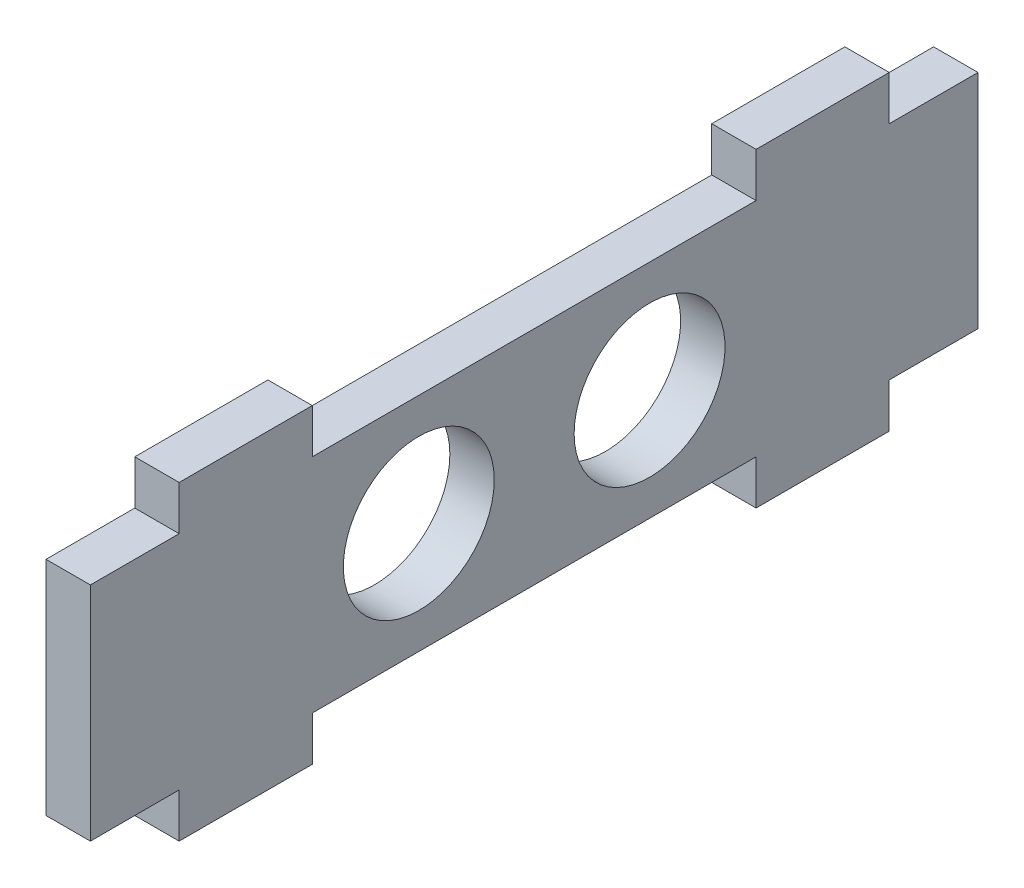
SolidWorks part; units mm, degrees
ref_plane "Front Plane" through (0, 0, 0) normal (0, 0, 1) x (1, 0, 0)
ref_plane "Top Plane" through (0, 0, 0) normal (0, 1, 0) x (1, 0, 0)
ref_plane "Right Plane" through (0, 0, 0) normal (1, 0, 0) x (0, 0, -1)
sketch "Sketch2" plane through (0, 0, 0) normal (1, 0, 0) x (0, 0, -1)
  line L0 (0, -4.3058) -> (0, 5.8448) construction
  line L1 (-50, -12.5) -> (-40, -12.5)
  line L2 (-50, -12.5) -> (-50, 12.5)
  line L3 (-50, 12.5) -> (-40, 12.5)
  line L4 (50, -12.5) -> (50, 12.5)
  line L5 (-50, -12.5) -> (50, 12.5) construction
  line L6 (-50, 12.5) -> (50, -12.5) construction
  line L7 (-25, 12.5) -> (25, 12.5)
  line L9 (-40, 12.5) -> (-40, 17.5)
  line L10 (-40, 17.5) -> (-25, 17.5)
  line L11 (-25, 12.5) -> (-25, 17.5)
  line L13 (40, 12.5) -> (40, 17.5)
  line L14 (40, 17.5) -> (25, 17.5)
  line L15 (25, 12.5) -> (25, 17.5)
  line L16 (-40, -12.5) -> (-40, -17.5)
  line L17 (-40, -17.5) -> (-25, -17.5)
  line L18 (-25, -12.5) -> (-25, -17.5)
  line L19 (25, -12.5) -> (25, -17.5)
  line L20 (40, -12.5) -> (40, -17.5)
  line L21 (40, -17.5) -> (25, -17.5)
  line L22 (-25, -12.5) -> (25, -12.5)
  line L23 (40, -12.5) -> (50, -12.5)
  line L24 (40, 12.5) -> (50, 12.5)
  circle A0 centre (-13, 0) radius 8.5
  circle A1 centre (13, 0) radius 8.5
  point P0 (0, 0)
  dimension "D6" = 17
  dimension "D1" = 100
  dimension "D2" = 25
  dimension "D3" = 15
  dimension "D4" = 10
  dimension "D5" = 5
  dimension "D7" = 13
extrude "Boss-Extrude1" add sketch "Sketch2" along normal blind 5
